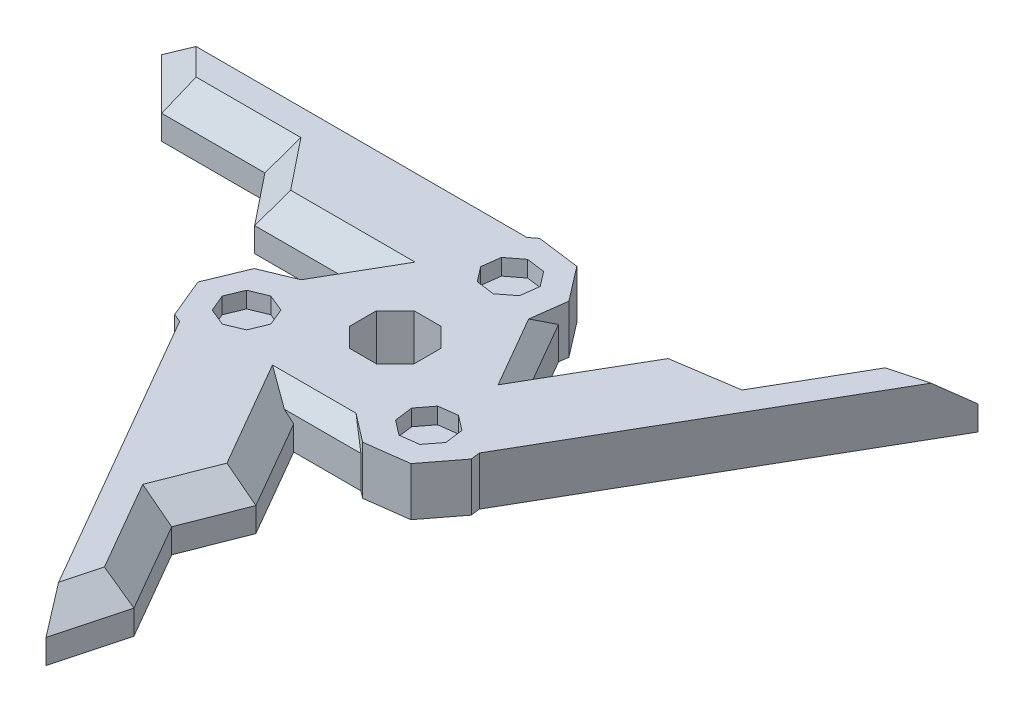
SolidWorks part; units mm, degrees
ref_plane "Front Plane" through (0, 0, 0) normal (0, 0, 1) x (1, 0, 0)
ref_plane "Top Plane" through (0, 0, 0) normal (0, 1, 0) x (1, 0, 0)
ref_plane "Right Plane" through (0, 0, 0) normal (1, 0, 0) x (0, 0, -1)
sketch "Sketch1" plane through (0, 0, 0) normal (0, 1, 0) x (1, 0, 0)
  line L1 (2, 0.8284) -> (0.8284, 2)
  line L2 (0.8284, 2) -> (-0.8284, 2)
  line L3 (-0.8284, 2) -> (-2, 0.8284)
  line L4 (-2, 0.8284) -> (-2, -0.8284)
  line L5 (-2, -0.8284) -> (-0.8284, -2)
  line L6 (-0.8284, -2) -> (0.8284, -2)
  line L7 (0.8284, -2) -> (2, -0.8284)
  line L8 (2, -0.8284) -> (2, 0.8284)
  line L9 (-3.6172, 0) -> (-1.8086, -3.1326)
  line L10 (-1.8086, -3.1326) -> (1.8086, -3.1326)
  line L11 (1.8086, -3.1326) -> (3.6172, 0)
  line L12 (3.6172, 0) -> (1.8086, 3.1326)
  line L13 (1.8086, 3.1326) -> (-1.8086, 3.1326)
  line L14 (-1.8086, 3.1326) -> (-3.6172, 0)
  circle A0 centre (0, 0) radius 2 construction
  circle A1 centre (0, 0) radius 3.1326 construction
extrude "Boss-Extrude2" add sketch "Sketch1" along normal blind 3
sketch "Sketch3" plane through (0, 0, 0) normal (0, 1, 0) x (1, 0, 0)
  line L0 (-1.8086, -3.1326) -> (-3.6172, 0)
  line L1 (0, -6.2652) -> (3.1914, -11.7929)
  line L2 (1.8086, -3.1326) -> (-1.8086, -3.1326)
  line L3 (5.4258, 3.1326) -> (8.6172, 8.6603)
  line L5 (3.6172, -6.2652) -> (7.2345, -6.2652)
  line L6 (7.2345, -6.2652) -> (9.0431, -3.1326)
  line L9 (3.6172, 0) -> (1.8086, -3.1326)
  line L10 (9.0431, -3.1326) -> (16.5431, 9.8578)
  line L11 (12.5802, 9.259) -> (8.6172, 8.6603)
  line L12 (1.7285, -15.5242) -> (3.1914, -11.7929)
  line L13 (9.0431, -3.1326) -> (7.2345, 0) [skipped]
  line L14 (5.4258, 0) -> (3.6172, 0) [skipped]
  line L15 (-7.2345, -6.2652) -> (0.2655, -19.2556)
  line L16 (-9.0431, -3.1326) -> (-7.2345, -6.2652)
  line L17 (-7.2345, 0) -> (-9.0431, -3.1326)
  line L19 (-1.8086, 3.1326) -> (1.8086, 3.1326)
  line L20 (-5.4258, 3.1326) -> (-11.8086, 3.1326)
  line L21 (-14.3086, 6.2652) -> (-11.8086, 3.1326)
  line L22 (-1.8086, 9.3978) -> (-16.8086, 9.3978)
  line L23 (1.8086, 9.3978) -> (-1.8086, 9.3978)
  line L24 (3.6172, 6.2652) -> (1.8086, 9.3978)
  line L26 (3.6172, -6.2652) -> (0, -6.2652)
  line L27 (-7.2345, 0) -> (-5.4258, 3.1326)
  line L28 (-3.6172, 0) -> (-1.8086, 3.1326)
  line L29 (3.6172, 6.2652) -> (5.4258, 3.1326)
  line L30 (1.8086, 3.1326) -> (3.6172, 0)
  line L33 (1.8086, -3.1326) -> (3.6172, -6.2652) [skipped]
  line L34 (-16.8086, 9.3978) -> (-23.8086, 9.3978)
  line L35 (-23.8086, 9.3978) -> (-20.676, 6.2652)
  line L36 (-20.676, 6.2652) -> (-14.3086, 6.2652)
  line L37 (16.5431, 9.8578) -> (20.0431, 15.9199)
  line L38 (15.7638, 14.7733) -> (12.5802, 9.259)
  line L39 (20.0431, 15.9199) -> (15.7638, 14.7733)
  line L40 (0.2655, -19.2556) -> (3.7655, -25.3178)
  line L41 (4.9122, -21.0386) -> (1.7285, -15.5242)
  line L42 (3.7655, -25.3178) -> (4.9122, -21.0386)
  point P28 (0, 0)
  point P38 (0, 0)
  point P50 (0, 0)
  dimension "D1" = 3
  dimension "D2" = 3
  dimension "D3" = 3
extrude "Boss-Extrude3" add sketch "Sketch3" along normal blind 3
chamfer "Chamfer1" distance 1.5 angle 45 12 edges at (17.9035, 3, -15.3466) (14.172, 3, -12.0162) (10.5987, 3, -8.9596) (7.0215, 3, -5.8964) (4.3389, 3, 23.1782) (3.3203, 3, 18.2814) (2.4599, 3, 13.6586) (1.5957, 3, 9.029) (-8.6172, 3, -3.1326) (-13.0586, 3, -4.6989) (-17.4923, 3, -6.2652) (-22.2423, 3, -7.8315)
sketch "Sketch4" plane through (0, 0, 0) normal (0, 1, 0) x (1, 0, 0)
  line L0 (-9.0431, -3.1326) -> (-5.5707, -3.1326)
  line L1 (-6.7984, -0.1688) -> (-6.7984, -6.0965)
  line L2 (-9.0431, -3.1326) -> (-8.026, -5.5879)
  line L3 (-8.026, -5.5879) -> (-6.7984, -6.0965)
  line L8 (-6.7984, -0.1688) -> (-8.026, -0.6773)
  line L9 (-8.026, -0.6773) -> (-9.0431, -3.1326)
  line L10 (-3.1154, -0.6773) -> (-4.343, -0.1688) [skipped]
  line L11 (-2.0984, -3.1326) -> (-2.6069, -1.9049) [skipped]
  line L12 (-3.1154, -5.5879) -> (-2.6069, -4.3603) [skipped]
  line L13 (-5.5707, -6.605) -> (-4.343, -6.0965) [skipped]
  line L14 (3.4265, 7.2894) -> (1.8086, 9.3978)
  line L15 (3.253, 5.972) -> (3.4265, 7.2894)
  line L16 (3.253, 5.972) -> (-1.8805, 8.9358)
  line L17 (-0.8263, 9.7447) -> (-1.8805, 8.9358)
  line L18 (1.8086, 9.3978) -> (-0.8263, 9.7447)
  line L19 (4.5996, -6.6121) -> (7.2345, -6.2652)
  line L20 (3.5453, -5.8032) -> (4.5996, -6.6121)
  line L21 (3.5453, -5.8032) -> (8.6789, -2.8393)
  line L22 (8.8523, -4.1568) -> (8.6789, -2.8393)
  line L23 (7.2345, -6.2652) -> (8.8523, -4.1568)
  arc A0 (-6.7984, -0.1688) -> (-6.7984, -6.0965) centre (-5.5707, -3.1326) ccw construction
  point P27 (0, 0)
  dimension "D1" = 3
extrude "Boss-Extrude4" add sketch "Sketch4" along normal blind 3 contours L9 L8 L1 L3 L2 | L21 L22 L23 L19 L20 | L16 L17 L18 L14 L15
ref_plane "Plane1" through (0, 3, 0) normal (0, 1, 0) x (1, 0, 0)
sketch "Sketch6" plane through (0, 3, 0) normal (0, 1, 0) x (1, 0, 0)
  line L0 (1.0586, 8.0988) -> (-0.0796, 8.2486)
  line L1 (-0.0796, 8.2486) -> (-0.9904, 7.5498)
  line L2 (-7.5431, -3.1326) -> (-7.1037, -4.1933)
  line L3 (-7.1037, -4.1933) -> (-6.0431, -4.6326)
  line L4 (-6.0431, -4.6326) -> (-4.9824, -4.1933)
  line L5 (-4.9824, -4.1933) -> (-4.5431, -3.1326)
  line L6 (-4.5431, -3.1326) -> (-4.9824, -2.072)
  line L7 (-4.9824, -2.072) -> (-6.0431, -1.6326)
  line L8 (-6.0431, -1.6326) -> (-7.1037, -2.072)
  line L9 (-7.1037, -2.072) -> (-7.5431, -3.1326)
  line L10 (-0.9904, 7.5498) -> (-1.1403, 6.4115)
  line L11 (-1.1403, 6.4115) -> (-0.4414, 5.5007)
  line L12 (-0.4414, 5.5007) -> (0.6968, 5.3509)
  line L13 (0.6968, 5.3509) -> (1.6077, 6.0498)
  line L14 (1.6077, 6.0498) -> (1.7575, 7.188)
  line L15 (1.7575, 7.188) -> (1.0586, 8.0988)
  line L16 (6.4845, -4.9662) -> (7.1833, -4.0554)
  line L17 (7.1833, -4.0554) -> (7.0335, -2.9171)
  line L18 (7.0335, -2.9171) -> (6.1227, -2.2183)
  line L19 (6.1227, -2.2183) -> (4.9845, -2.3681)
  line L20 (4.9845, -2.3681) -> (4.2856, -3.2789)
  line L21 (4.2856, -3.2789) -> (4.4354, -4.4171)
  line L22 (4.4354, -4.4171) -> (5.3462, -5.116)
  line L23 (5.3462, -5.116) -> (6.4845, -4.9662)
  circle A0 centre (-6.0431, -3.1326) radius 1.3858 construction
  circle A1 centre (0.3086, 6.7998) radius 1.3858 construction
  circle A2 centre (5.7345, -3.6671) radius 1.3858 construction
  point P33 (0, 0)
  dimension "D1" = 3
extrude "Cut-Extrude1" cut sketch "Sketch6" against normal blind 1
chamfer "Chamfer2" distance 1 angle 45 3 edges at (1.2077, 3, 6.2652) (-6.0297, 3, -2.0867) (4.822, 3, -4.1785)
